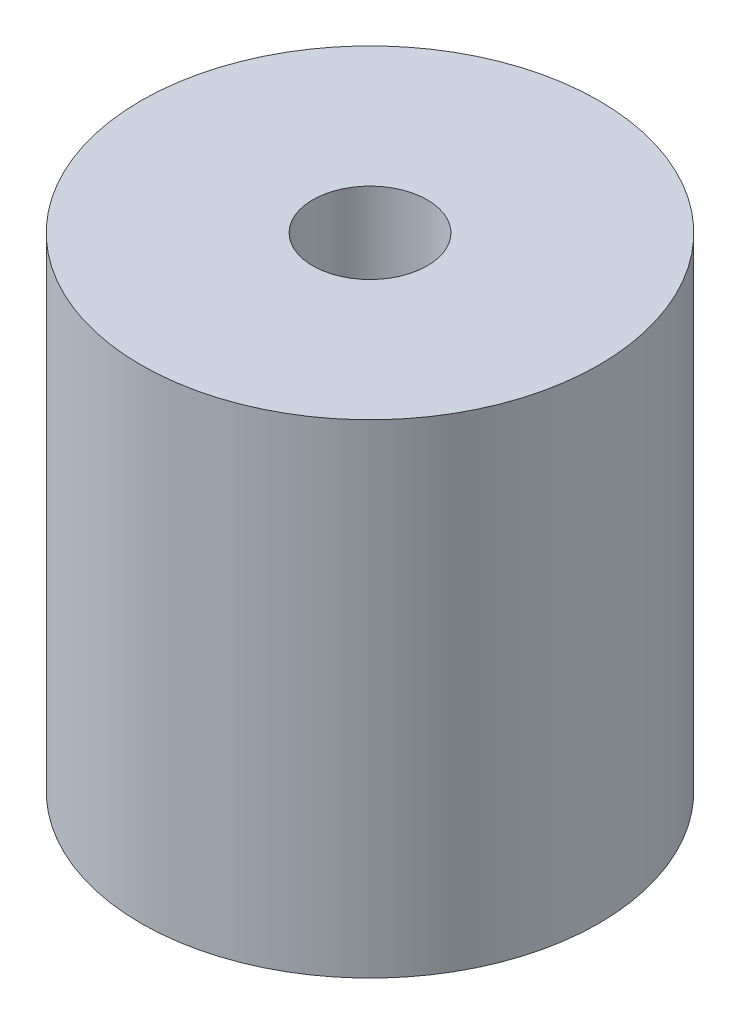
SolidWorks part; units mm, degrees
ref_plane "Front" through (0, 0, 0) normal (0, 0, 1) x (1, 0, 0)
ref_plane "Top" through (0, 0, 0) normal (0, 1, 0) x (1, 0, 0)
ref_plane "Right" through (0, 0, 0) normal (1, 0, 0) x (0, 0, -1)
sketch "Sketch1" plane through (0, 0, 0) normal (0, 1, 0) x (1, 0, 0)
  circle A0 centre (0, 0) radius 1.5875
  circle A1 centre (0, 0) radius 6.35
  dimension "D1" = 3.175
  dimension "D2" = 12.7
extrude "Boss-Extrude1" add sketch "Sketch1" along normal blind 13.41
